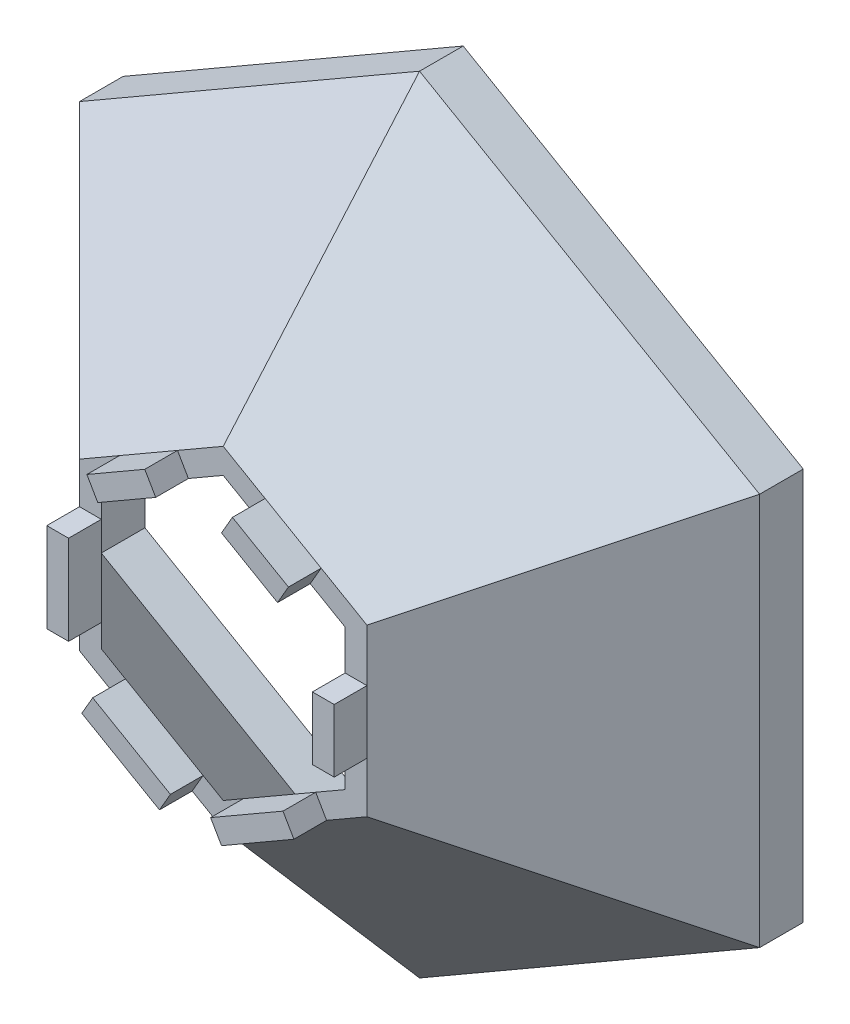
SolidWorks part; units mm, degrees
ref_plane "Спереди" through (0, 0, 0) normal (0, 0, 1) x (1, 0, 0)
ref_plane "Сверху" through (0, 0, 0) normal (0, 1, 0) x (1, 0, 0)
ref_plane "Справа" through (0, 0, 0) normal (1, 0, 0) x (0, 0, -1)
sketch "Skizze1" plane through (0, 0, 0) normal (0, 0, 1) x (1, 0, 0)
  line L1 (0, 18) -> (-15.5885, 9)
  line L2 (-15.5885, 9) -> (-15.5885, -9)
  line L3 (-15.5885, -9) -> (0, -18)
  line L4 (0, -18) -> (15.5885, -9)
  line L5 (15.5885, -9) -> (15.5885, 9)
  line L6 (15.5885, 9) -> (0, 18)
  circle A0 centre (0, 0) radius 15.5885 construction
  dimension "D1" = 18
extrude "Aufsatz-Linear austragen1" add sketch "Skizze1" along normal blind 10 draft 45
sketch "Skizze3" plane through (0, 0, 0) normal (0, 0, -1) x (-1, 0, 0)
  line L0 (0, 18) -> (15.5885, 9) construction
  line L1 (0, -16.8453) -> (14.5885, -8.4226)
  line L2 (14.5885, -8.4226) -> (14.5885, 8.4226)
  line L3 (14.5885, 8.4226) -> (0, 16.8453)
  line L4 (0, 16.8453) -> (-14.5885, 8.4226)
  line L5 (-14.5885, 8.4226) -> (-14.5885, -8.4226)
  line L6 (-14.5885, -8.4226) -> (0, -16.8453)
  circle A0 centre (0, 0) radius 14.5885 construction
  dimension "D1" = 1
extrude "Schnitt-Linear austragen1" cut sketch "Skizze3" against normal blind 10 draft 45
sketch "Skizze4" plane through (0, 0, 10) normal (0, 0, 1) x (1, 0, 0)
  line L1 (8.6487, -9.3733) -> (-9.8081, -9.3733)
  line L2 (8.6487, -9.3733) -> (8.6487, 9.2399)
  line L3 (8.6487, 9.2399) -> (-9.8081, 9.2399)
  line L4 (-9.8081, -9.3733) -> (-9.8081, 9.2399)
extrude "Schnitt-Linear austragen2" cut sketch "Skizze4" against normal blind 1
sketch "Skizze5" plane through (0, 0, 0) normal (0, 0, -1) x (-1, 0, 0)
  line L0 (0, 16.8453) -> (-14.5885, 8.4226) construction
  line L1 (-14.5885, 8.4226) -> (-14.5885, -8.4226) construction
  line L2 (-14.5885, -8.4226) -> (0, -16.8453) construction
  line L3 (0, -16.8453) -> (14.5885, -8.4226) construction
  line L4 (14.5885, -8.4226) -> (14.5885, 8.4226) construction
  line L5 (14.5885, 8.4226) -> (0, 16.8453) construction
  line L6 (0, 16.8453) -> (-14.5885, 8.4226)
  line L7 (-14.5885, 8.4226) -> (-14.5885, -8.4226)
  line L8 (-14.5885, -8.4226) -> (0, -16.8453)
  line L9 (0, -16.8453) -> (14.5885, -8.4226)
  line L10 (14.5885, -8.4226) -> (14.5885, 8.4226)
  line L11 (14.5885, 8.4226) -> (0, 16.8453)
extrude "Linear-Austragen-Dünn1" add sketch "Skizze5" along normal blind 2 thin
sketch "Skizze6" plane through (0, 0, 9) normal (0, 0, 1) x (1, 0, 0)
  line L0 (0, 7.6077) -> (-6.5885, 3.8038) construction
  line L1 (-4.25, 3.9993) -> (-4.75, 4.8653)
  line L2 (-5.5885, 3.2265) -> (0, 6.453) construction
  line L3 (-4.75, 4.8653) -> (-2.0954, 6.3979)
  line L4 (-2.0954, 6.3979) -> (-1.5954, 5.5319)
  line L5 (-1.5954, 5.5319) -> (-4.25, 3.9993)
  line L6 (-4.25, 3.9993) -> (-4.5869, 4.4811)
  line L7 (1.4217, 5.6322) -> (1.9217, 6.4982)
  line L8 (0, 6.453) -> (5.5885, 3.2265) construction
  line L9 (6.5885, 3.8038) -> (0, 7.6077) construction
  line L10 (1.9217, 6.4982) -> (4.4897, 5.0156)
  line L11 (4.4897, 5.0156) -> (3.9897, 4.1495)
  line L12 (3.9897, 4.1495) -> (1.4217, 5.6322)
  line L13 (5.5885, 1.4023) -> (6.5885, 1.4023)
  line L14 (5.5885, 3.2265) -> (5.5885, -3.2265) construction
  line L15 (6.5885, -3.8038) -> (6.5885, 3.8038) construction
  line L16 (6.5885, 1.4023) -> (6.5885, -1.482)
  line L17 (6.5885, -1.482) -> (5.5885, -1.482)
  line L18 (5.5885, -1.482) -> (5.5885, 1.4023)
  line L19 (4.2397, -4.0052) -> (4.7397, -4.8712)
  line L20 (5.5885, -3.2265) -> (0, -6.453) construction
  line L21 (0, -7.6077) -> (6.5885, -3.8038) construction
  line L22 (4.7397, -4.8712) -> (1.4217, -6.7869)
  line L23 (1.4217, -6.7869) -> (0.9217, -5.9209)
  line L24 (0.9217, -5.9209) -> (4.2397, -4.0052)
  line L25 (-0.9217, -5.9209) -> (-1.4217, -6.7869)
  line L26 (0, -6.453) -> (-5.5885, -3.2265) construction
  line L27 (-6.5885, -3.8038) -> (0, -7.6077) construction
  line L28 (-1.4217, -6.7869) -> (-4.5, -5.0096)
  line L29 (-4.5, -5.0096) -> (-4.982, -4.7313)
  line L30 (-4.982, -4.7313) -> (-4.482, -3.8653)
  line L31 (-4.482, -3.8653) -> (-0.9217, -5.9209)
  line L32 (-5.5885, -2.1805) -> (-6.5885, -2.1805)
  line L33 (-5.5885, -3.2265) -> (-5.5885, 3.2265) construction
  line L34 (-6.5885, 3.8038) -> (-6.5885, -3.8038) construction
  line L35 (-6.5885, -2.1805) -> (-6.5885, 1.9157)
  line L36 (-6.5885, 1.9157) -> (-5.5885, 1.9157)
  line L37 (-5.5885, 1.9157) -> (-5.5885, -2.1805)
  line L38 (-5.5885, -2.1805) -> (-6.1842, -2.166)
  line M1 (5.5885, -3.2265) -> (0, -6.453)
  line M2 (0, -6.453) -> (-5.5885, -3.2265)
  line M3 (-5.5885, -3.2265) -> (-5.5885, 3.2265)
  line M4 (-5.5885, 3.2265) -> (0, 6.453)
  line M5 (0, 6.453) -> (5.5885, 3.2265)
  line M6 (5.5885, 3.2265) -> (5.5885, -3.2265)
  line M7 (6.5885, 3.8038) -> (0, 7.6077)
  line M8 (0, 7.6077) -> (-6.5885, 3.8038)
  line M9 (-6.5885, 3.8038) -> (-6.5885, -3.8038)
  line M10 (-6.5885, -3.8038) -> (0, -7.6077)
  line M11 (0, -7.6077) -> (6.5885, -3.8038)
  line M12 (6.5885, -3.8038) -> (6.5885, 3.8038)
extrude "Aufsatz-Linear austragen2" add sketch "Skizze6" along normal blind 1.5 contours L36 L32 M9 M3 | L4 L1 M8 M4 | L11 L7 M7 M5 | L17 L13 M12 M6 | L23 L19 M11 M1 | L30 L25 M10 M2
